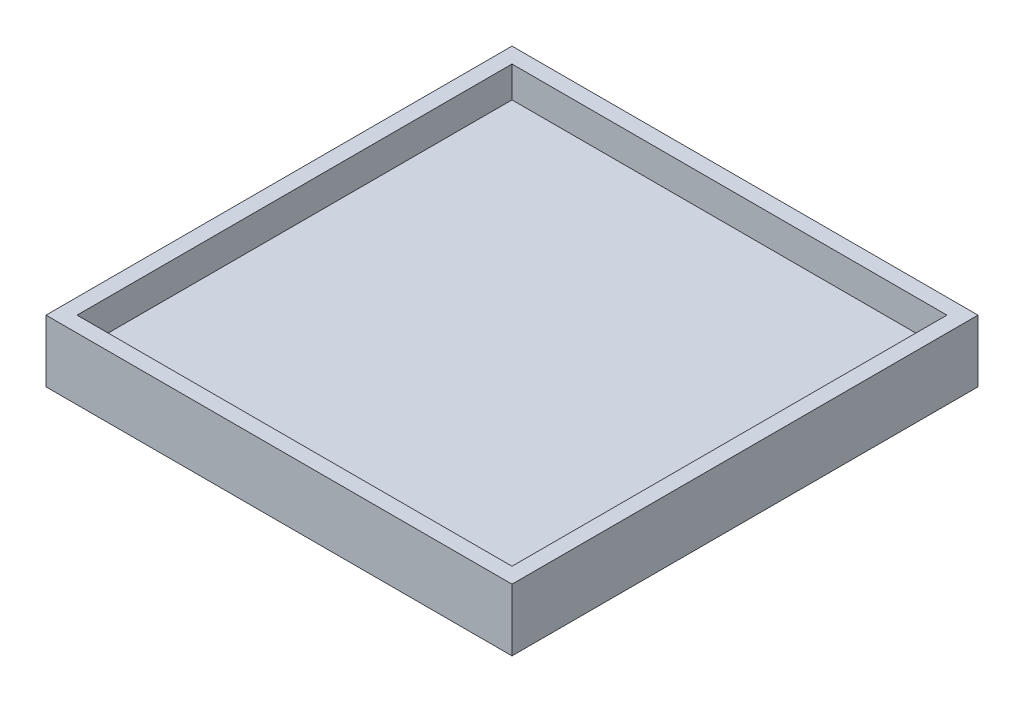
SolidWorks part; units mm, degrees
ref_plane "Front Plane" through (0, 0, 0) normal (0, 0, 1) x (1, 0, 0)
ref_plane "Top Plane" through (0, 0, 0) normal (0, 1, 0) x (1, 0, 0)
ref_plane "Right Plane" through (0, 0, 0) normal (1, 0, 0) x (0, 0, -1)
sketch "Sketch1" plane through (0, 0, 0) normal (0, 1, 0) x (1, 0, 0)
  line L1 (-36.5412, -35.6874) -> (39.6588, -35.6874)
  line L2 (-36.5412, -35.6874) -> (-36.5412, 40.5126)
  line L3 (-36.5412, 40.5126) -> (39.6588, 40.5126)
  line L4 (39.6588, -35.6874) -> (39.6588, 40.5126)
  dimension "D1" = 76.2
extrude "Boss-Extrude1" add sketch "Sketch1" along normal blind 10.16 contours L1 L4 L3 L2
sketch "Sketch4" plane through (0, 10.16, 0) normal (0, 1, 0) x (1, 0, 0)
  line L0 (-36.5412, 40.5126) -> (39.6588, 40.5126) construction
  line L1 (-34.0012, 37.9726) -> (37.1188, 37.9726)
  line L2 (-34.0012, 37.9726) -> (-34.0012, -33.1474)
  line L3 (-34.0012, -33.1474) -> (37.1188, -33.1474)
  line L4 (37.1188, 37.9726) -> (37.1188, -33.1474)
  line L5 (-36.5412, -35.6874) -> (-36.5412, 40.5126) construction
  dimension "D1" = 71.12
  dimension "D2" = 2.54
  dimension "D3" = 2.54
extrude "Cut-Extrude1" cut sketch "Sketch4" against normal blind 5.08
sketch "Sketch5" plane through (0, 5.08, 0) normal (0, 1, 0) x (1, 0, 0)
  line L0 (-34.0012, 34.9246) -> (0.0348, 34.9246)
  line L1 (37.1188, 37.9726) -> (-34.0012, 37.9726) construction
  line L2 (0.0348, 34.9246) -> (0.0348, -2.1594)
  line L3 (0.0348, -2.1594) -> (3.0828, -2.1594)
  line L4 (3.0828, -2.1594) -> (3.0828, 37.9726)
  line L5 (3.0828, 37.9726) -> (-34.0012, 37.9726)
  line L6 (-34.0012, 37.9726) -> (-34.0012, 34.9246)
  dimension "D1" = 34.036
  dimension "D2" = 3.048
  dimension "D3" = 37.084
  dimension "D4" = 3.048
